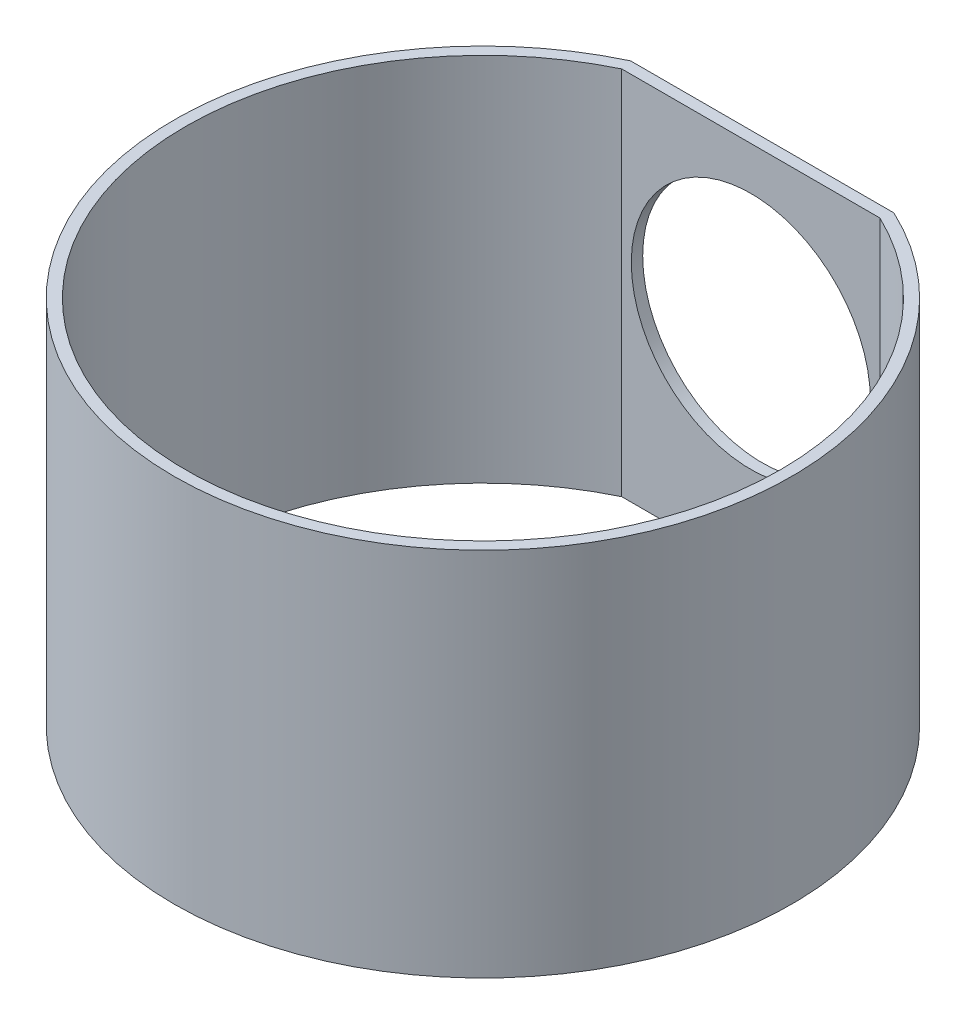
SolidWorks part; units mm, degrees
material "PTFE (general)"
ref_plane "Front Plane" through (0, 0, 0) normal (0, 0, 1) x (1, 0, 0)
ref_plane "Top Plane" through (0, 0, 0) normal (0, 1, 0) x (1, 0, 0)
ref_plane "Right Plane" through (0, 0, 0) normal (1, 0, 0) x (0, 0, -1)
sketch "Sketch1" plane through (0, 0, 0) normal (0, 1, 0) x (-1, 0, 0)
  line L0 (27.4356, -42.9353) -> (38.9356, -42.9353) construction
  line L1 (27.4356, -42.9353) -> (15.9356, -42.9353) construction
  line L2 (15.9356, -42.9353) -> (15.9356, -66.7989) construction
  line L3 (38.9356, -42.9353) -> (38.9356, -66.7989) construction
  line L4 (15.9356, -66.7989) -> (38.9356, -66.7989)
  line L5 (15.7058, -67.8149) -> (39.1653, -67.8149)
  arc A0 (38.9356, -66.7989) -> (15.9356, -66.7989) centre (27.4356, -42.9353) ccw
  arc A1 (39.1653, -67.8149) -> (15.7058, -67.8149) centre (27.4356, -42.9353) ccw
  dimension "D2" = 11.5
  dimension "D1" = 11.5
  dimension "D3" = 52.98
  dimension "D4" = 1.016
extrude "Boss-Extrude1" add sketch "Sketch1" along normal blind 33
sketch "Sketch2" plane through (0, 0, -67.8149) normal (0, 0, -1) x (-1, 0, 0)
  line L0 (27.4356, 0) -> (27.4356, 18.5)
  line L1 (15.7058, 0) -> (39.1653, 0) construction
  circle A0 centre (27.4356, 18.5) radius 10.65
  dimension "D2" = 21.3
  dimension "D1" = 18.5
extrude "Cut-Extrude1" cut sketch "Sketch2" against normal blind 10
